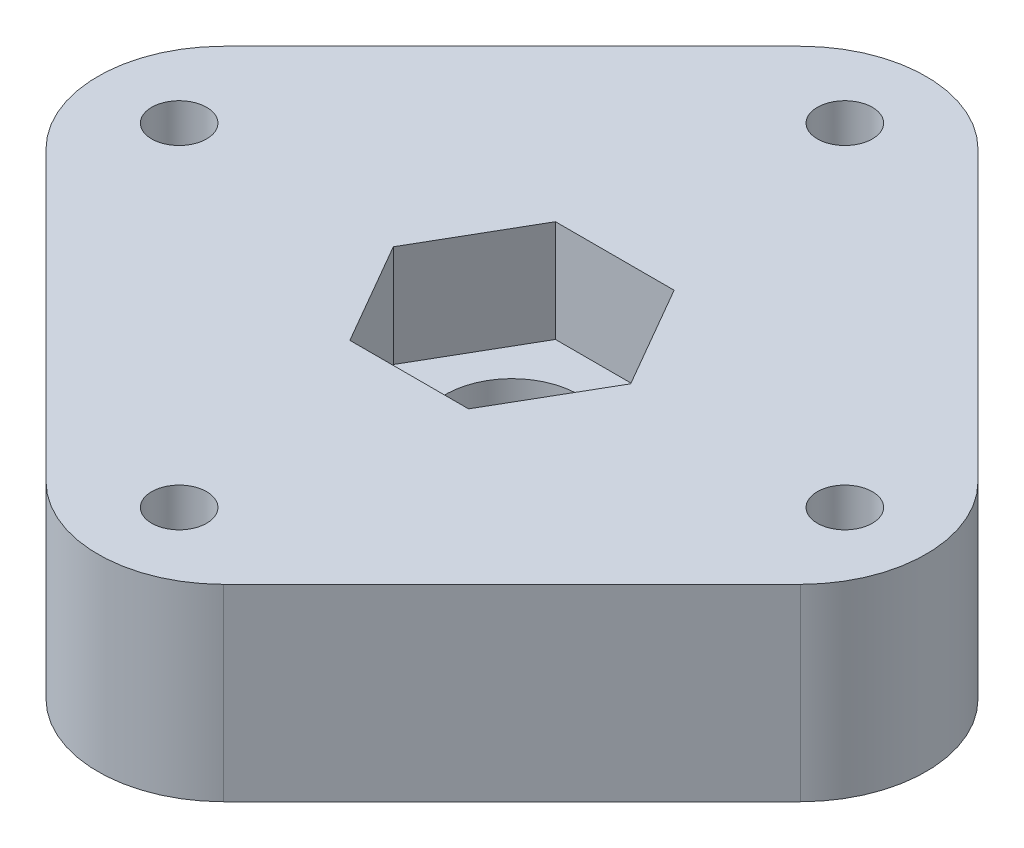
SolidWorks part; units mm, degrees
ref_plane "Спереди" through (0, 0, 0) normal (0, 0, 1) x (1, 0, 0)
ref_plane "Сверху" through (0, 0, 0) normal (0, 1, 0) x (1, 0, 0)
ref_plane "Справа" through (0, 0, 0) normal (1, 0, 0) x (0, 0, -1)
sketch "Эскиз1" plane through (0, 0, 0) normal (0, 1, 0) x (1, 0, 0)
  line L4 (0, 0) -> (29.6985, 0) construction
  line L5 (5.6569, -24.0416) -> (24.0416, -5.6569)
  line L6 (24.0416, 5.6569) -> (5.6569, 24.0416)
  line L7 (-5.6569, 24.0416) -> (-24.0416, 5.6569)
  line L8 (-24.0416, -5.6569) -> (-5.6569, -24.0416)
  line L10 (21.2132, 0) -> (0, 21.2132) construction
  line L11 (0, 21.2132) -> (-21.2132, 0) construction
  line L12 (-21.2132, 0) -> (0, -21.2132) construction
  line L13 (0, -21.2132) -> (21.2132, 0) construction
  line L14 (0, 14.1421) -> (-14.1421, 0) construction
  line L15 (-14.1421, 0) -> (0, -14.1421) construction
  line L16 (0, -14.1421) -> (14.1421, 0) construction
  line L17 (14.1421, 0) -> (0, 14.1421) construction
  circle A0 centre (0, 0) radius 21 construction
  circle A1 centre (21.2132, 0) radius 1.75
  circle A2 centre (14.1421, 0) radius 1.75 construction
  circle A3 centre (0, -14.1421) radius 1.75 construction
  circle A4 centre (0, -21.2132) radius 1.75
  circle A5 centre (-14.1421, 0) radius 1.75 construction
  circle A6 centre (-21.2132, 0) radius 1.75
  circle A7 centre (0, 14.1421) radius 1.75 construction
  circle A8 centre (0, 21.2132) radius 1.75
  circle A11 centre (0, 0) radius 15 construction
  circle A12 centre (0, 0) radius 10 construction
  arc A13 (24.0416, 5.6569) -> (24.0416, -5.6569) centre (18.3848, 0) cw
  arc A14 (5.6569, -24.0416) -> (-5.6569, -24.0416) centre (0, -18.3848) cw
  arc A15 (-24.0416, -5.6569) -> (-24.0416, 5.6569) centre (-18.3848, 0) cw
  arc A16 (-5.6569, 24.0416) -> (5.6569, 24.0416) centre (0, 18.3848) cw
  circle A17 centre (0, 0) radius 4.25
  point P36 (-29.6985, 0)
  point P39 (0, 29.6985)
  dimension "D2" = 3.5
  dimension "D3" = 3.5
  dimension "D5" = 30
  dimension "D7" = 8
  dimension "D8" = 8.5
  dimension "D1" = 42
  dimension "D6" = 20
  dimension "D4" = 4
extrude "Бобышка-Вытянуть1" add sketch "Эскиз1" along normal blind 12
sketch "Эскиз2" plane through (0, 12, 0) normal (0, 1, 0) x (1, 0, 0)
  line L1 (3.7816, -6.55) -> (7.5633, 0)
  line L2 (7.5633, 0) -> (3.7816, 6.55)
  line L3 (3.7816, 6.55) -> (-3.7816, 6.55)
  line L4 (-3.7816, 6.55) -> (-7.5633, 0)
  line L5 (-7.5633, 0) -> (-3.7816, -6.55)
  line L6 (-3.7816, -6.55) -> (3.7816, -6.55)
  circle A0 centre (0, 0) radius 6.55 construction
  dimension "D1" = 13.1
extrude "Вырез-Вытянуть1" cut sketch "Эскиз2" against normal blind 6.5
sketch "Эскиз4" plane through (0, 0, 0) normal (0, -1, 0) x (1, 0, 0)
  line L0 (24.0632, -1.6454) -> (24.0632, 1.6454)
  line L1 (-1.6454, 18.3632) -> (1.6454, 18.3632)
  line L2 (1.6454, 18.3632) -> (3.2909, 21.2132)
  line L3 (3.2909, 21.2132) -> (1.6454, 24.0632)
  line L4 (1.6454, 24.0632) -> (-1.6454, 24.0632)
  line L5 (-1.6454, 24.0632) -> (-3.2909, 21.2132)
  line L6 (-3.2909, 21.2132) -> (-1.6454, 18.3632)
  line L7 (21.2132, -3.2909) -> (24.0632, -1.6454)
  line L8 (18.3632, -1.6454) -> (21.2132, -3.2909)
  line L9 (18.3632, 1.6454) -> (18.3632, -1.6454)
  line L10 (21.2132, 3.2909) -> (18.3632, 1.6454)
  line L11 (24.0632, 1.6454) -> (21.2132, 3.2909)
  line L12 (-1.6454, -24.0632) -> (1.6454, -24.0632)
  line L13 (-3.2909, -21.2132) -> (-1.6454, -24.0632)
  line L14 (-1.6454, -18.3632) -> (-3.2909, -21.2132)
  line L15 (1.6454, -18.3632) -> (-1.6454, -18.3632)
  line L16 (3.2909, -21.2132) -> (1.6454, -18.3632)
  line L17 (1.6454, -24.0632) -> (3.2909, -21.2132)
  line L18 (-24.0632, 1.6454) -> (-24.0632, -1.6454)
  line L19 (-21.2132, 3.2909) -> (-24.0632, 1.6454)
  line L20 (-18.3632, 1.6454) -> (-21.2132, 3.2909)
  line L21 (-18.3632, -1.6454) -> (-18.3632, 1.6454)
  line L22 (-21.2132, -3.2909) -> (-18.3632, -1.6454)
  line L23 (-24.0632, -1.6454) -> (-21.2132, -3.2909)
  circle A0 centre (0, 21.2132) radius 2.85 construction
  dimension "D1" = 5.7
  dimension "D2" = 4
extrude "Вырез-Вытянуть2" cut sketch "Эскиз4" against normal blind 2.5
equation "\"print_offset\"= 0.5"
equation "\"tape_width\"=51"
equation "\"tape_thikness\"=5"
equation "\"tape_distance\"=5"
equation "\"screw_d\"=3"
equation "\"screw_hh_d\"=5.3"
equation "\"nut_d\"=5.5"
equation "\"nut_h\"=2.5"
equation "\"sitting_screws\"=30"
equation "\"mount_size\"=42"
equation "\"D1@Эскиз1\"=\"mount_size\""
equation "\"D2@Эскиз1\"=\"screw_d\"+\"print_offset\""
equation "\"D3@Эскиз1\"=\"D2@Эскиз1\""
equation "\"D5@Эскиз1\"=\"sitting_screws\""
equation "\"D6@Эскиз1\"=\"D5@Эскиз1\"*2/3"
